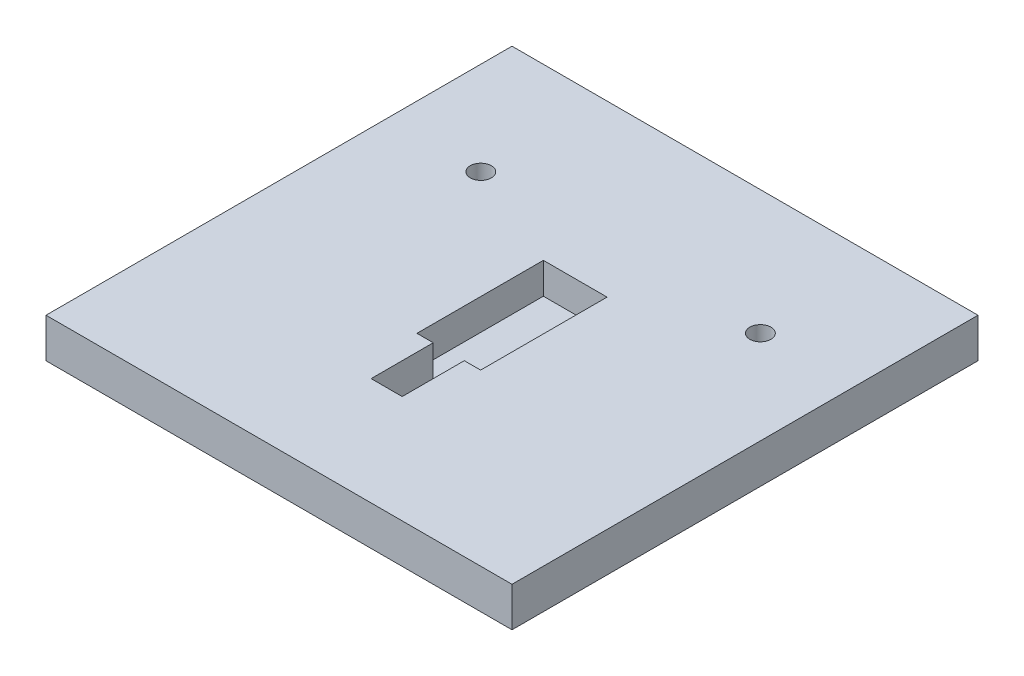
SolidWorks part; units mm, degrees
material "Liga 1060"
ref_plane "Plano frontal" through (0, 0, 0) normal (0, 0, 1) x (1, 0, 0)
ref_plane "Plano superior" through (0, 0, 0) normal (0, 1, 0) x (1, 0, 0)
ref_plane "Plano direito" through (0, 0, 0) normal (1, 0, 0) x (0, 0, -1)
sketch "Esboço1" plane through (0, 0, 0) normal (0, 1, 0) x (1, 0, 0)
  line L1 (75, -75) -> (-75, -75)
  line L2 (75, -75) -> (75, 75)
  line L3 (75, 75) -> (-75, 75)
  line L4 (-75, -75) -> (-75, 75)
  line L5 (75, -75) -> (-75, 75) construction
  line L6 (75, 75) -> (-75, -75) construction
  point P0 (0, 0)
  point P6 (0, 0)
  dimension "D1" = 150
  dimension "D2" = 150
extrude "Ressalto-extrusão2" add sketch "Esboço1" along normal blind 12.7
sketch "Esboço2" plane through (0, 12.7, 0) normal (0, 1, 0) x (1, 0, 0)
  line L0 (-5, -20.35) -> (5, -20.35) construction
  line L1 (10.25, -20.35) -> (-10.25, -20.35) construction
  line L2 (10.25, -20.35) -> (10.25, 20.35)
  line L3 (10.25, 20.35) -> (-10.25, 20.35)
  line L4 (-10.25, -20.35) -> (-10.25, 20.35)
  line L5 (10.25, -20.35) -> (-10.25, 20.35) construction
  line L6 (10.25, 20.35) -> (-10.25, -20.35) construction
  line L7 (-5, -20.35) -> (-5, -30.35)
  line L8 (5, -20.35) -> (5, -30.35)
  line L9 (-5, -30.35) -> (5, -30.35)
  line L10 (-10.25, -20.35) -> (-5, -20.35)
  line L11 (5, -20.35) -> (10.25, -20.35)
  point P0 (0, 0)
  point P6 (0, -20.35)
  point P9 (0, -20.35)
  dimension "D1" = 40.7
  dimension "D2" = 20.5
  dimension "D3" = 10
  dimension "D4" = 10
extrude "Corte-extrusão1" cut sketch "Esboço2" against normal blind 10
sketch "Esboço4" plane through (0, 12.7, 0) normal (0, 1, 0) x (1, 0, 0)
  line L0 (-5, -30.35) -> (5, -30.35)
  line L1 (-5, -30.35) -> (-5, -40.35)
  line L2 (5, -30.35) -> (5, -40.35)
  line L3 (-5, -40.35) -> (5, -40.35)
  dimension "D1" = 10
extrude "Corte-extrusão2" cut sketch "Esboço4" against normal through all
sketch "Esboço5" plane through (0, 0, 0) normal (0, -1, 0) x (-1, 0, 0)
  line L0 (-75, 34.96) -> (75, 34.96) construction
  line L1 (-75, -75) -> (-75, 75) construction
  line L2 (75, 75) -> (75, -75) construction
  line L3 (-75, 75) -> (75, 75) construction
  circle A0 centre (-45, 34.96) radius 3
  circle A1 centre (45, 34.96) radius 3
  dimension "D4" = 6
  dimension "D1" = 40.04
  dimension "D2" = 30
  dimension "D3" = 30
extrude "Corte-extrusão3" cut sketch "Esboço5" against normal up to surface (12.7 mm away) up to face at (0, 12.7, 15.175)
hole_wizard "Furo roscado de M83" positions "Esboço8" profile "Esboço9" tap size "M8" standard "ISO" end condition through all
sketch "Esboço8" plane through (0, 12.7, 0) normal (0, 1, 0) x (1, 0, 0)
  point P0 (45, 34.96)
  point P3 (-45, 34.96)
sketch "Esboço9" plane through (45, 12.7, -34.96) normal (1, 0, 0) x (0, 0, 1)
  line L0 (0, 0) -> (0, 12.7)
  line L1 (0, 12.7) -> (3.4, 12.7)
  line L2 (3.4, 12.7) -> (3.4, 0)
  line L5 (3.4, 0) -> (0, 0)
  line L11 (0, -6.35) -> (0, 107.95) construction
  dimension "Thru Tap Drill Dia." = 6.8
  dimension "Thru Tap Drill Depth" = 12.7
cosmetic thread "Rosca de furo5" parameters "D2"=8
cosmetic thread "Rosca de furo6" parameters "D2"=8
